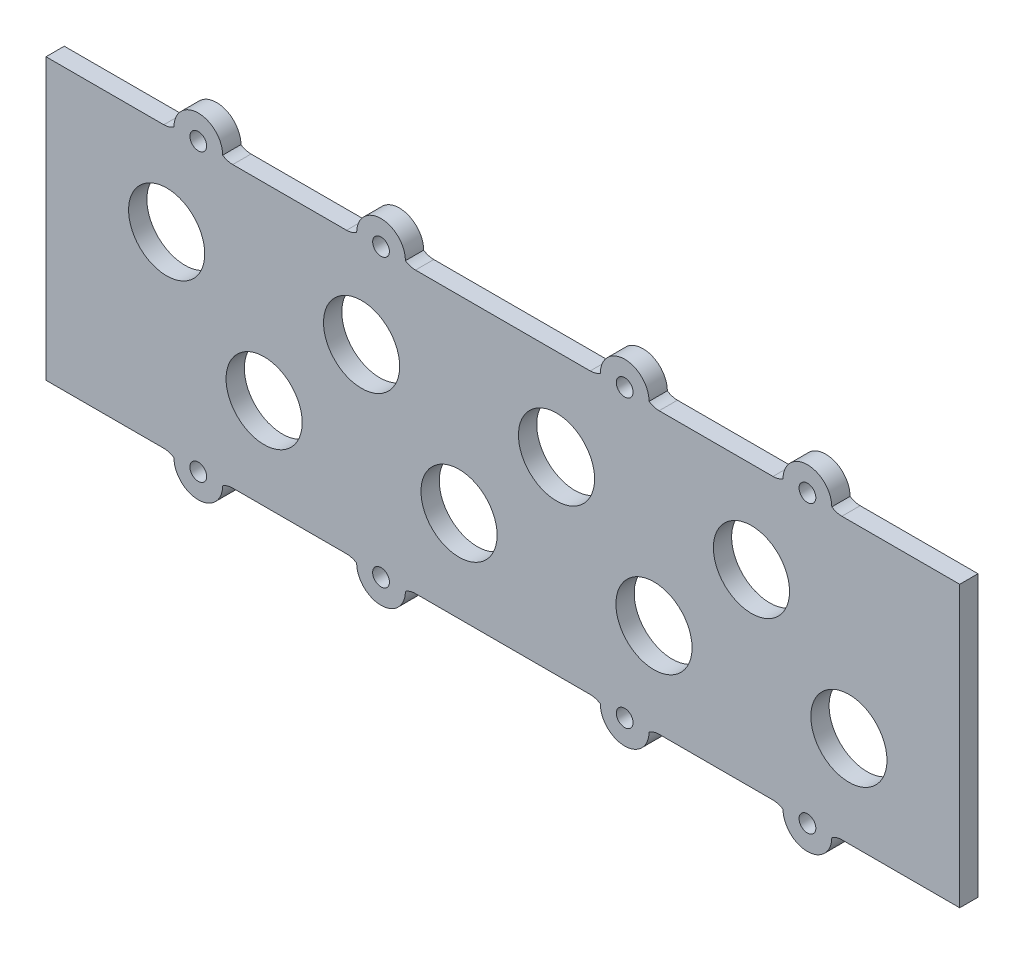
SolidWorks part; units mm, degrees
material "Aircraft Ply"
ref_plane "Front Plane" through (0, 0, 0) normal (0, 0, 1) x (1, 0, 0)
ref_plane "Top Plane" through (0, 0, 0) normal (0, 1, 0) x (1, 0, 0)
ref_plane "Right Plane" through (0, 0, 0) normal (1, 0, 0) x (0, 0, -1)
sketch "Sketch1" plane through (0, 0, 0) normal (0, 0, 1) x (1, 0, 0)
  line L0 (-75, 8) -> (75, 8) construction
  line L1 (-75, 0) -> (75, 0) construction
  line L8 (-75, 23) -> (-75, -23)
  line L9 (-44.3417, -23) -> (-25.6583, -23)
  line L10 (-14.3417, -23) -> (14.3417, -23)
  line L11 (25.6583, -23) -> (44.3417, -23)
  line L12 (75, -23) -> (75, 23)
  line L13 (44.3417, 23) -> (25.6583, 23)
  line L14 (14.3417, 23) -> (-14.3417, 23)
  line L15 (-25.6583, 23) -> (-44.3417, 23)
  line L16 (-75, 23) -> (-75, -23)
  line L17 (-44.3417, -23) -> (-25.6583, -23)
  line L18 (-14.3417, -23) -> (14.3417, -23)
  line L19 (25.6583, -23) -> (44.3417, -23)
  line L20 (75, -23) -> (75, 23)
  line L21 (44.3417, 23) -> (25.6583, 23)
  line L22 (14.3417, 23) -> (-14.3417, 23)
  line L23 (-25.6583, 23) -> (-44.3417, 23)
  line L30 (-75, -23) -> (-55.6583, -23)
  line L31 (-75, -23) -> (-55.6583, -23)
  line L32 (55.6583, -23) -> (75, -23)
  line L33 (55.6583, -23) -> (75, -23)
  line L34 (75, 23) -> (55.6583, 23)
  line L35 (75, 23) -> (55.6583, 23)
  line L36 (-55.6583, 23) -> (-75, 23)
  line L37 (-55.6583, 23) -> (-75, 23)
  circle A0 centre (-50, 23.5) radius 1.375 construction
  circle A1 centre (-20, 23.5) radius 1.375 construction
  circle A2 centre (20, 23.5) radius 1.375 construction
  circle A3 centre (50, 23.5) radius 1.375 construction
  circle A4 centre (50, -23.5) radius 1.375 construction
  circle A5 centre (20, -23.5) radius 1.375 construction
  circle A6 centre (-20, -23.5) radius 1.375 construction
  circle A7 centre (-50, -23.5) radius 1.375 construction
  circle A8 centre (-50, -23.5) radius 1.375
  circle A9 centre (-20, -23.5) radius 1.375
  circle A10 centre (20, -23.5) radius 1.375
  circle A11 centre (50, -23.5) radius 1.375
  circle A12 centre (50, 23.5) radius 1.375
  circle A13 centre (20, 23.5) radius 1.375
  circle A14 centre (-20, 23.5) radius 1.375
  circle A15 centre (-50, 23.5) radius 1.375
  circle A16 centre (-55.1927, 8) radius 6.25
  circle A17 centre (-23.1927, 8) radius 6.25
  circle A18 centre (8.8073, 8) radius 6.25
  circle A19 centre (40.8073, 8) radius 6.25
  circle A20 centre (-39.1927, -8) radius 6.25
  circle A21 centre (-7.1927, -8) radius 6.25
  circle A22 centre (24.8073, -8) radius 6.25
  circle A23 centre (56.8073, -8) radius 6.25
  arc A29 (-54, -23.5) -> (-55.6583, -23) centre (-55.6583, -26) ccw
  arc A30 (-54, -23.5) -> (-46, -23.5) centre (-50, -23.5) ccw
  arc A31 (-44.3417, -23) -> (-46, -23.5) centre (-44.3417, -26) ccw
  arc A32 (-24, -23.5) -> (-25.6583, -23) centre (-25.6583, -26) ccw
  arc A33 (-24, -23.5) -> (-16, -23.5) centre (-20, -23.5) ccw
  arc A34 (-14.3417, -23) -> (-16, -23.5) centre (-14.3417, -26) ccw
  arc A35 (16, -23.5) -> (14.3417, -23) centre (14.3417, -26) ccw
  arc A36 (16, -23.5) -> (24, -23.5) centre (20, -23.5) ccw
  arc A37 (25.6583, -23) -> (24, -23.5) centre (25.6583, -26) ccw
  arc A38 (46, -23.5) -> (44.3417, -23) centre (44.3417, -26) ccw
  arc A39 (46, -23.5) -> (54, -23.5) centre (50, -23.5) ccw
  arc A40 (55.6583, -23) -> (54, -23.5) centre (55.6583, -26) ccw
  arc A43 (54, 23.5) -> (55.6583, 23) centre (55.6583, 26) ccw
  arc A44 (54, 23.5) -> (46, 23.5) centre (50, 23.5) ccw
  arc A45 (44.3417, 23) -> (46, 23.5) centre (44.3417, 26) ccw
  arc A46 (24, 23.5) -> (25.6583, 23) centre (25.6583, 26) ccw
  arc A47 (24, 23.5) -> (16, 23.5) centre (20, 23.5) ccw
  arc A48 (14.3417, 23) -> (16, 23.5) centre (14.3417, 26) ccw
  arc A49 (-16, 23.5) -> (-14.3417, 23) centre (-14.3417, 26) ccw
  arc A50 (-16, 23.5) -> (-24, 23.5) centre (-20, 23.5) ccw
  arc A51 (-25.6583, 23) -> (-24, 23.5) centre (-25.6583, 26) ccw
  arc A52 (-46, 23.5) -> (-44.3417, 23) centre (-44.3417, 26) ccw
  arc A53 (-46, 23.5) -> (-54, 23.5) centre (-50, 23.5) ccw
  arc A54 (-55.6583, 23) -> (-54, 23.5) centre (-55.6583, 26) ccw
  arc A57 (-54, -23.5) -> (-55.6583, -23) centre (-55.6583, -26) ccw
  arc A58 (-54, -23.5) -> (-46, -23.5) centre (-50, -23.5) ccw
  arc A59 (-44.3417, -23) -> (-46, -23.5) centre (-44.3417, -26) ccw
  arc A60 (-24, -23.5) -> (-25.6583, -23) centre (-25.6583, -26) ccw
  arc A61 (-24, -23.5) -> (-16, -23.5) centre (-20, -23.5) ccw
  arc A62 (-14.3417, -23) -> (-16, -23.5) centre (-14.3417, -26) ccw
  arc A63 (16, -23.5) -> (14.3417, -23) centre (14.3417, -26) ccw
  arc A64 (16, -23.5) -> (24, -23.5) centre (20, -23.5) ccw
  arc A65 (25.6583, -23) -> (24, -23.5) centre (25.6583, -26) ccw
  arc A66 (46, -23.5) -> (44.3417, -23) centre (44.3417, -26) ccw
  arc A67 (46, -23.5) -> (54, -23.5) centre (50, -23.5) ccw
  arc A68 (55.6583, -23) -> (54, -23.5) centre (55.6583, -26) ccw
  arc A71 (54, 23.5) -> (55.6583, 23) centre (55.6583, 26) ccw
  arc A72 (54, 23.5) -> (46, 23.5) centre (50, 23.5) ccw
  arc A73 (44.3417, 23) -> (46, 23.5) centre (44.3417, 26) ccw
  arc A74 (24, 23.5) -> (25.6583, 23) centre (25.6583, 26) ccw
  arc A75 (24, 23.5) -> (16, 23.5) centre (20, 23.5) ccw
  arc A76 (14.3417, 23) -> (16, 23.5) centre (14.3417, 26) ccw
  arc A77 (-16, 23.5) -> (-14.3417, 23) centre (-14.3417, 26) ccw
  arc A78 (-16, 23.5) -> (-24, 23.5) centre (-20, 23.5) ccw
  arc A79 (-25.6583, 23) -> (-24, 23.5) centre (-25.6583, 26) ccw
  arc A80 (-46, 23.5) -> (-44.3417, 23) centre (-44.3417, 26) ccw
  arc A81 (-46, 23.5) -> (-54, 23.5) centre (-50, 23.5) ccw
  arc A82 (-55.6583, 23) -> (-54, 23.5) centre (-55.6583, 26) ccw
  dimension "D2" = 12.5
  dimension "D3" = 8
  dimension "D1" = 0
  dimension "D4" = 4
  dimension "D5" = 2
extrude "Boss-Extrude1" add sketch "Sketch1" along normal blind 3
sketch "Sketch2" plane through (0, 0, 3) normal (0, 0, 1) x (1, 0, 0)
  line L0 (-55.1927, 8) -> (-39.1927, -8) construction
  line L1 (-48.449, 14.7437) -> (-32.449, -1.2563)
  line L2 (-61.9364, 1.2563) -> (-45.9364, -14.7437)
  line L3 (-23.1927, 8) -> (-7.1927, -8) construction
  line L4 (-16.449, 14.7437) -> (-0.449, -1.2563)
  line L5 (-29.9364, 1.2563) -> (-13.9364, -14.7437)
  line L6 (24.8073, -8) -> (8.8073, 8) construction
  line L7 (18.0636, -14.7437) -> (2.0636, 1.2563)
  line L8 (31.551, -1.2563) -> (15.551, 14.7437)
  line L9 (40.8073, 8) -> (56.8073, -8) construction
  line L10 (47.551, 14.7437) -> (63.551, -1.2563)
  line L11 (34.0636, 1.2563) -> (50.0636, -14.7437)
  arc A10 (-48.449, 14.7437) -> (-61.9364, 1.2563) centre (-55.1927, 8) ccw
  arc A11 (-45.9364, -14.7437) -> (-32.449, -1.2563) centre (-39.1927, -8) ccw
  arc A12 (-16.449, 14.7437) -> (-29.9364, 1.2563) centre (-23.1927, 8) ccw
  arc A13 (-13.9364, -14.7437) -> (-0.449, -1.2563) centre (-7.1927, -8) ccw
  arc A14 (18.0636, -14.7437) -> (31.551, -1.2563) centre (24.8073, -8) ccw
  arc A15 (15.551, 14.7437) -> (2.0636, 1.2563) centre (8.8073, 8) ccw
  arc A16 (47.551, 14.7437) -> (34.0636, 1.2563) centre (40.8073, 8) ccw
  arc A17 (50.0636, -14.7437) -> (63.551, -1.2563) centre (56.8073, -8) ccw
  text T0 "      1" font "Century Gothic" height in points 18
  point P2 (-47.1927, 0)
  point P7 (-15.1927, 0)
  point P14 (16.8073, 0)
  point P21 (48.8073, 0)
